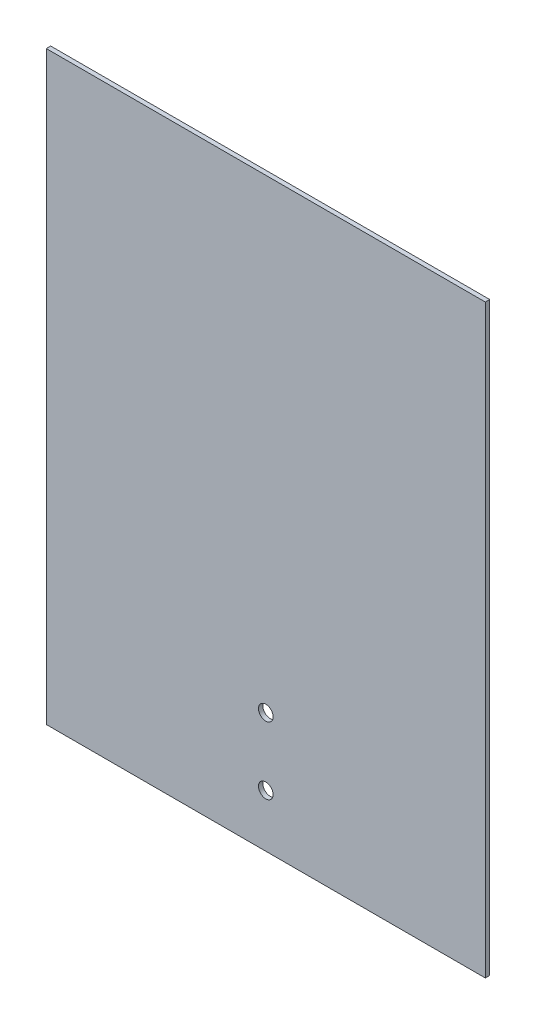
SolidWorks part; units mm, degrees
ref_plane "前视基准面" through (0, 0, 0) normal (0, 0, 1) x (1, 0, 0)
ref_plane "上视基准面" through (0, 0, 0) normal (0, 1, 0) x (1, 0, 0)
ref_plane "右视基准面" through (0, 0, 0) normal (1, 0, 0) x (0, 0, -1)
sketch "草图1" plane through (0, 0, 0) normal (0, 0, 1) x (1, 0, 0)
  line L1 (-75, -100) -> (75, -100)
  line L2 (-75, -100) -> (-75, 100)
  line L3 (-75, 100) -> (75, 100)
  line L4 (75, -100) -> (75, 100)
  line L5 (-75, -100) -> (75, 100) construction
  line L6 (-75, 100) -> (75, -100) construction
  point P0 (0, 0)
extrude "凸台-拉伸1" add sketch "草图1" along normal blind 1.5
sketch "草图2" plane through (0, 0, 1.5) normal (0, 0, 1) x (1, 0, 0)
  line L0 (0, -100) -> (0, -51) construction
  line L1 (-75, -100) -> (75, -100) construction
  line L2 (0, -51) -> (0, -59) construction
  line L3 (0, -59) -> (0, -82) construction
  circle A0 centre (0, -59) radius 2.5
  circle A1 centre (0, -82) radius 2.5
  dimension "D1" = 18
  dimension "D2" = 5
  dimension "D3" = 5
  dimension "D4" = 8
  dimension "D5" = 49
extrude "切除-拉伸1" cut sketch "草图2" against normal blind 1.5
